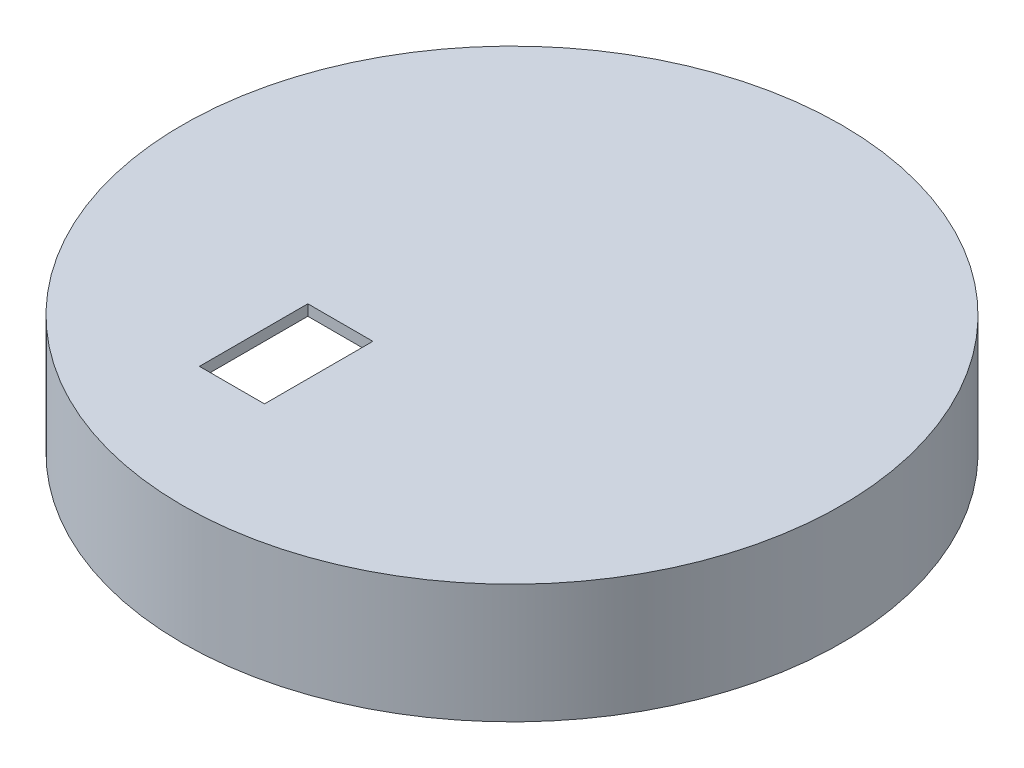
SolidWorks part; units mm, degrees
ref_plane "Ebene vorne" through (0, 0, 0) normal (0, 0, 1) x (1, 0, 0)
ref_plane "Ebene oben" through (0, 0, 0) normal (0, 1, 0) x (1, 0, 0)
ref_plane "Ebene rechts" through (0, 0, 0) normal (1, 0, 0) x (0, 0, -1)
sketch "Skizze1" plane through (0, 0, 0) normal (0, 1, 0) x (1, 0, 0)
  circle A0 centre (0, 0) radius 30.405
  circle A1 centre (0, 0) radius 28.405
  dimension "D1" = 60.81
  dimension "D2" = 2
extrude "Aufsatz-Linear austragen1" add sketch "Skizze1" along normal blind 10
sketch "Skizze2" plane through (0, 10, 0) normal (0, 1, 0) x (1, 0, 0)
  circle A0 centre (0, 0) radius 30.405
  circle A1 centre (0, 0) radius 30.405 construction
extrude "Aufsatz-Linear austragen2" add sketch "Skizze2" along normal blind 1
sketch "Skizze3" plane through (0, 11, 0) normal (0, 1, 0) x (1, 0, 0)
  line L0 (0, 0) -> (-46.4213, 0) construction
  line L1 (-30.405, 0) -> (-30.405, 15.213) construction
  line L2 (0, 0) -> (0, 17.3597) construction
  line L3 (-26.405, 3.75) -> (-30.1729, 3.75)
  line L4 (-26.405, -3.75) -> (-30.1729, -3.75)
  line L5 (26.405, -3.75) -> (30.1729, -3.75)
  line L6 (26.405, 3.75) -> (30.1729, 3.75)
  line L7 (-30.1729, 3.75) -> (-34.1632, 0.7281)
  line L8 (-34.1632, 0.7281) -> (-30.1729, -3.75)
  line L9 (34.1632, 0.7281) -> (30.1729, -3.75)
  line L10 (30.1729, 3.75) -> (34.1632, 0.7281)
  circle A0 centre (-26.405, 0) radius 2.75
  circle A2 centre (0, 0) radius 30.405 construction
  circle A3 centre (26.405, 0) radius 2.75
  arc A4 (-26.405, 3.75) -> (-26.405, -3.75) centre (-26.405, 0) cw
  arc A5 (26.405, 3.75) -> (26.405, -3.75) centre (26.405, 0) ccw
  circle M8 centre (0, 0) radius 30.405
  dimension "D1" = 5.5
  dimension "D3" = 1
  dimension "D2" = 4
extrude "Schnitt-Linear austragen1" [suppressed] cut sketch "Skizze3" against normal through all contours A0 | A4 L3 L4 A0 M8 | L7 L8 M8 | A3 | L6 A5 L5 A3 M8 | L10 L9 M8
sketch "Skizze4" plane through (0, 10, 0) normal (0, -1, 0) x (1, 0, 0)
  line L0 (0, 0) -> (39.4101, 0) construction
  line L1 (30.405, 0) -> (30.405, 9.5037) construction
  line L2 (0, 0) -> (0, 10.4457) construction
  circle A0 centre (0, 0) radius 30.405 construction
  circle A1 centre (27.605, 0) radius 1.5 construction
  arc A2 (28.1268, 3.9658) -> (28.1268, -3.9658) centre (27.605, 0) ccw
  circle A3 centre (0, 0) radius 28.405 construction
  arc A4 (-28.1268, 3.9658) -> (-28.1268, -3.9658) centre (-27.605, 0) cw
  circle M4 centre (0, 0) radius 28.405
  dimension "D1" = 3
  dimension "D3" = 2.5
  dimension "D2" = 2.8
extrude "Aufsatz-Linear austragen3" add sketch "Skizze4" along normal up to surface (10 mm away) contours A4 M4 | A2 M4 up to face at (0, 0, 30.405)
sketch "Skizze5" plane through (0, 0, 0) normal (0, -1, 0) x (1, 0, 0)
  line L0 (0, 0) -> (40.9284, 0)
  line L1 (30.405, 0) -> (30.405, 7.0978) construction
  line L2 (0, 0) -> (0, 11.2853)
  circle A0 centre (27.605, 0) radius 1.5
  circle A1 centre (0, 0) radius 30.405 construction
  circle A2 centre (-27.605, 0) radius 1.5
  dimension "D1" = 3
  dimension "D2" = 2.8
extrude "Schnitt-Linear austragen2" cut sketch "Skizze5" against normal blind 10 contours A2 | L0 A0 | L0 A0
sketch "Skizze6" plane through (0, 11, 0) normal (0, 1, 0) x (1, 0, 0)
  line L1 (-10.3288, -18.5083) -> (-4.3288, -18.5083)
  line L2 (-10.3288, -18.5083) -> (-10.3288, -8.5083)
  line L3 (-10.3288, -8.5083) -> (-4.3288, -8.5083)
  line L4 (-4.3288, -18.5083) -> (-4.3288, -8.5083)
  line L5 (-10.3288, -18.5083) -> (-4.3288, -8.5083) construction
  line L6 (-10.3288, -8.5083) -> (-4.3288, -18.5083) construction
  point P0 (-7.3288, -13.5083)
  dimension "D1" = 10
  dimension "D2" = 6
extrude "Schnitt-Linear austragen3" cut sketch "Skizze6" against normal blind 10
